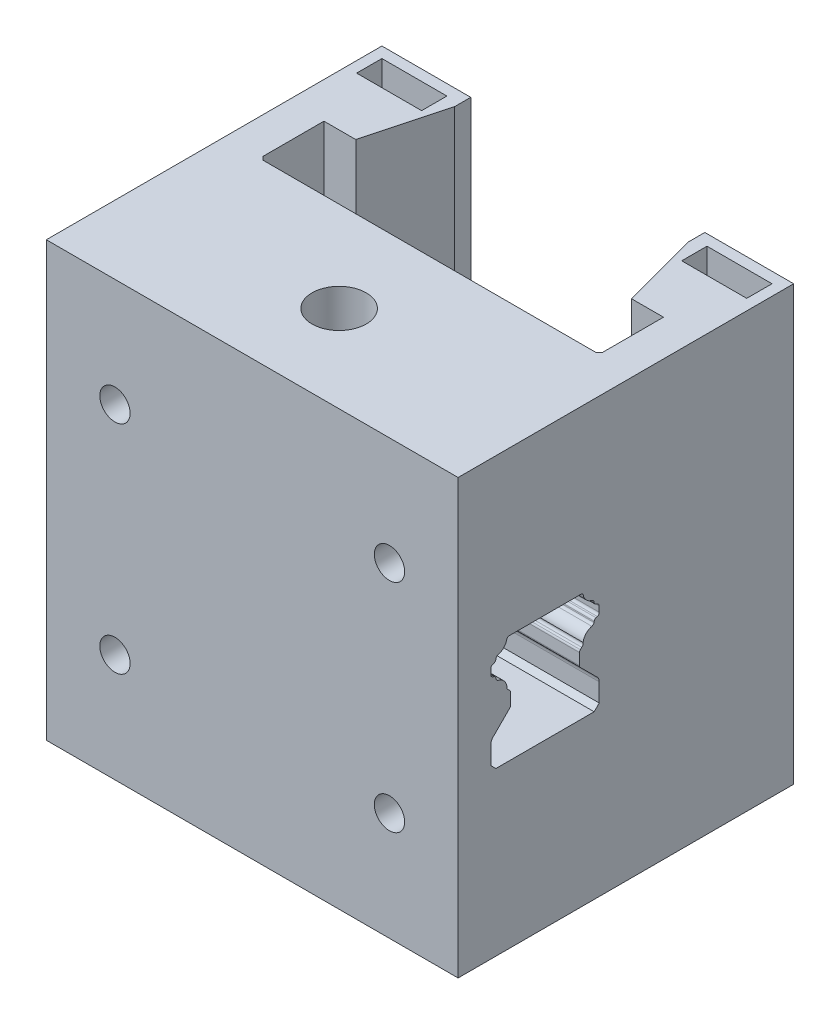
SolidWorks part; units mm, degrees
ref_plane "Front Plane" through (0, 0, 0) normal (0, 0, 1) x (1, 0, 0)
ref_plane "Top Plane" through (0, 0, 0) normal (0, 1, 0) x (1, 0, 0)
ref_plane "Right Plane" through (0, 0, 0) normal (1, 0, 0) x (0, 0, -1)
sketch "Sketch1" plane through (0, 0, 0) normal (0, 1, 0) x (1, 0, 0)
  line L0 (23.07, -9.85) -> (-23.07, -9.85)
  line L1 (-23.5, -9.42) -> (-23.07, -9.85)
  line L2 (-23.5, -9.42) -> (-23.5, -0.95)
  line L7 (-19.0939, -0.95) -> (-23.5, -0.95)
  line L8 (-19.0939, -0.95) -> (-19, -0.5997)
  line L9 (-16.2, 9.85) -> (-19, -0.5997)
  line L10 (16.2, 9.85) -> (-16.2, 9.85)
  line L11 (23.07, -9.85) -> (23.5, -9.42)
  line L12 (23.5, -2.9) -> (23.5, -9.42)
  line L13 (23.5, -2.9) -> (23.5, -0.95)
  line L15 (19.0939, -0.95) -> (23.5, -0.95)
  line L16 (19.0939, -0.95) -> (19, -0.5997)
  line L17 (16.2, 9.85) -> (19, -0.5997)
  line L18 (-28.5, -14.85) -> (28.5, -14.85)
  line L19 (-28.5, -14.85) -> (-28.5, 13.85)
  line L20 (-28.5, 13.85) -> (28.5, 13.85)
  line L21 (28.5, -14.85) -> (28.5, 13.85)
  dimension "D1" = 5
  dimension "D2" = 5
  dimension "D3" = 5
  dimension "D4" = 4
extrude "Boss-Extrude1" add sketch "Sketch1" along normal blind 60
sketch "Sketch2" plane through (0, 0, 0) normal (0, -1, 0) x (1, 0, 0)
  line L0 (0, -25.3794) -> (0, 27.4746) construction
  line L1 (28.5, -8.0706) -> (19.5, -8.0706)
  line L2 (28.5, -8.0706) -> (28.5, -12.0706)
  line L3 (28.5, -12.0706) -> (19.5, -12.0706)
  line L4 (19.5, -8.0706) -> (19.5, -12.0706)
  line L5 (-19.5, -8.0706) -> (-19.5, -12.0706)
  line L6 (-28.5, -12.0706) -> (-19.5, -12.0706)
  line L7 (-28.5, -8.0706) -> (-28.5, -12.0706)
  line L8 (-28.5, -8.0706) -> (-19.5, -8.0706)
  dimension "D1" = 9
  dimension "D2" = 4
extrude "Cut-Extrude1" cut sketch "Sketch2" against normal through all
sketch "Sketch5" plane through (0, 0, 0) normal (1, 0, 0) x (0, 0, -1)
  line L0 (-14.85, 23.2) -> (-14.85, 34.0815)
  line L1 (-15.55, 22.5) -> (-14.85, 23.2)
  line L2 (-29.15, 22.5) -> (-15.55, 22.5)
  line L3 (-29.85, 23.2) -> (-29.15, 22.5)
  line L4 (-29.85, 25.7434) -> (-29.85, 23.2)
  line L5 (-27.2372, 28.7704) -> (-29.5571, 26.4505)
  line L6 (-27.12, 30.6153) -> (-27.12, 29.0533)
  line L7 (-27.4316, 31.0926) -> (-27.2372, 30.8982)
  line L8 (-29.1562, 33.3541) -> (-29.1243, 33.2128)
  line L9 (-29.5857, 33.7052) -> (-29.4106, 33.6421)
  line L10 (-29.85, 34.8375) -> (-29.85, 34.0815)
  line L11 (-29.4277, 35.2633) -> (-29.5687, 35.2195)
  line L12 (-29.125, 35.7021) -> (-29.1553, 35.5612)
  line L13 (-27.399, 37.5) -> (-27.4361, 37.4629)
  line L14 (-17.301, 37.5) -> (-27.399, 37.5)
  line L15 (-17.2639, 37.4629) -> (-17.301, 37.5)
  line L16 (-15.5447, 35.5612) -> (-15.575, 35.7021)
  line L17 (-15.1313, 35.2195) -> (-15.2723, 35.2633)
  line L18 (-14.85, 34.0815) -> (-14.85, 60)
  line L19 (-15.2894, 33.6421) -> (-15.1143, 33.7052)
  line L20 (-15.5757, 33.2128) -> (-15.5438, 33.3541)
  line L21 (-17.4628, 30.8982) -> (-17.2684, 31.0926)
  line L22 (-17.58, 29.0533) -> (-17.58, 30.6153)
  line L23 (-15.1429, 26.4505) -> (-17.4628, 28.7704)
  line L24 (-14.85, 60) -> (-34.3805, 60)
  line L25 (-14.85, 30) -> (-29.85, 30) construction
  line L26 (-34.3805, 60) -> (-34.3805, 0)
  line L27 (-14.85, 34.0815) -> (-14.85, 30) construction
  line L28 (-34.3805, 0) -> (-14.85, 0)
  line L29 (-14.85, 0) -> (-14.85, 23.2)
  arc A0 (-14.85, 25.7434) -> (-15.1429, 26.4505) centre (-15.85, 25.7434) ccw
  arc A1 (-29.5571, 26.4505) -> (-29.85, 25.7434) centre (-28.85, 25.7434) ccw
  arc A2 (-27.2372, 28.7704) -> (-27.12, 29.0533) centre (-27.52, 29.0533) ccw
  arc A3 (-27.12, 30.6153) -> (-27.2372, 30.8982) centre (-27.52, 30.6153) ccw
  arc A4 (-27.6206, 31.5718) -> (-27.4316, 31.0926) centre (-27.2414, 31.4445) ccw
  arc A5 (-27.6206, 31.5718) -> (-28.8285, 32.9123) centre (-29.2062, 31.3576) ccw
  arc A6 (-29.1243, 33.2128) -> (-28.8285, 32.9123) centre (-28.7341, 33.301) ccw
  arc A7 (-29.1562, 33.3541) -> (-29.4106, 33.6421) centre (-29.5464, 33.2658) ccw
  arc A8 (-29.85, 34.0815) -> (-29.5857, 33.7052) centre (-29.45, 34.0815) ccw
  arc A9 (-29.5687, 35.2195) -> (-29.85, 34.8375) centre (-29.45, 34.8375) ccw
  arc A10 (-29.4277, 35.2633) -> (-29.1553, 35.5612) centre (-29.5464, 35.6453) ccw
  arc A11 (-28.8284, 36.0067) -> (-29.125, 35.7021) centre (-28.734, 35.618) ccw
  arc A12 (-28.8284, 36.0067) -> (-27.624, 37.3234) centre (-29.2062, 37.5614) ccw
  arc A13 (-27.4361, 37.4629) -> (-27.624, 37.3234) centre (-27.3021, 37.086) ccw
  arc A14 (-17.076, 37.3234) -> (-17.2639, 37.4629) centre (-17.3979, 37.086) ccw
  arc A15 (-17.076, 37.3234) -> (-15.8716, 36.0067) centre (-15.4938, 37.5614) ccw
  arc A16 (-15.575, 35.7021) -> (-15.8716, 36.0067) centre (-15.966, 35.618) ccw
  arc A17 (-15.5447, 35.5612) -> (-15.2723, 35.2633) centre (-15.1536, 35.6453) ccw
  arc A18 (-14.85, 34.8375) -> (-15.1313, 35.2195) centre (-15.25, 34.8375) ccw
  arc A19 (-15.1143, 33.7052) -> (-14.85, 34.0815) centre (-15.25, 34.0815) ccw
  arc A20 (-15.2894, 33.6421) -> (-15.5438, 33.3541) centre (-15.1536, 33.2658) ccw
  arc A21 (-15.8715, 32.9123) -> (-15.5757, 33.2128) centre (-15.9659, 33.301) ccw
  arc A22 (-15.8715, 32.9123) -> (-17.0794, 31.5718) centre (-15.4938, 31.3576) ccw
  arc A23 (-17.2684, 31.0926) -> (-17.0794, 31.5718) centre (-17.4586, 31.4445) ccw
  arc A24 (-17.4628, 30.8982) -> (-17.58, 30.6153) centre (-17.18, 30.6153) ccw
  arc A25 (-17.58, 29.0533) -> (-17.4628, 28.7704) centre (-17.18, 29.0533) ccw
  dimension "D1" = 15
  dimension "D2" = 7.5
extrude "Boss-Extrude2" add sketch "Sketch5" along normal mid plane 57 contours A18 L18 L24 L26 L28 L29 L1 L2 L3 L4 A1 L5 A2 L6 A3 L7 A4 A5 A6 L8 A7 L9 A8 L10 A9 L11 A10 L12 A11 A12 A13 L13 L14 L15 A14 A15 A16 L16 A17 L17 | L22 A25 L23 A0 L0 A19 L19 A20 L20 A21 A22 A23 L21 A24
sketch "Sketch6" plane through (0, 60, 0) normal (0, 1, 0) x (1, 0, 0)
  line L0 (0, 26.3935) -> (0, -49.3571) construction
  line L1 (28.5, 13.85) -> (-28.5, 13.85) construction
  line L2 (-7.75, 19.7454) -> (7.75, 19.7454)
  line L3 (-7.75, 19.7454) -> (-7.75, 4.3549)
  line L4 (-7.75, 4.3549) -> (7.75, 4.3549)
  line L5 (7.75, 19.7454) -> (7.75, 4.3549)
  dimension "D1" = 5.8954
  dimension "D2" = 15.5
extrude "Cut-Extrude2" cut sketch "Sketch6" against normal blind 80
sketch "Sketch9" plane through (0, 60, 0) normal (0, 1, 0) x (1, 0, 0)
  line L0 (-19.5, 13.85) -> (-19.5, 29.1706)
  line L1 (-19.5, 29.1706) -> (-28.5, 29.1706)
  line L2 (30.2, 1.2503) -> (30.2, 34.991) construction
  line L3 (-28.5, 23.1706) -> (-28.5, 8.0706) construction
  line L4 (-19.5, 12.0706) -> (-19.5, 8.0706) construction
  line L5 (-7.75, 13.85) -> (-28.5, 13.85) construction
  line L6 (-14.5, 13.85) -> (-14.5, 32.1706)
  line L7 (10, 28.7358) -> (570, 28.7358) construction
  line L10 (-14.5, 13.85) -> (-19.5, 13.85)
  line L11 (-19.25, 24.1706) -> (-28.75, 24.1706) construction
  line L12 (0, -34.3805) -> (0, 38.6423) construction
  line L13 (28.5, -34.3805) -> (-28.5, -34.3805) construction
  line L14 (-33.5, 26.1706) -> (-28.5, 26.1706)
  line L16 (-33.5, 32.1706) -> (-14.5, 32.1706)
  line L17 (-33.5, 26.1706) -> (-33.5, 32.1706)
  line L18 (-28.5, 26.1706) -> (-28.5, 29.1706)
  line L19 (28.5, 23.1706) -> (28.5, 8.0706) construction
  line L20 (30.2, 12.85) -> (30.2, 28.7358)
  line L21 (33.5, 12.85) -> (33.5, 32.1706)
  line L24 (33.5, 12.85) -> (30.2, 12.85)
  line L25 (14.5, 13.85) -> (19.5, 13.85)
  line L28 (14.5, 32.1706) -> (33.5, 32.1706)
  line L29 (14.5, 13.85) -> (14.5, 32.1706)
  line L31 (19.5, 28.7358) -> (30.2, 28.7358)
  line L32 (19.5, 13.85) -> (19.5, 28.7358)
  dimension "D1" = 5
  dimension "D2" = 3
  dimension "D3" = 3
  dimension "D4" = 5
  dimension "D5" = 5
extrude "Boss-Extrude5" add sketch "Sketch9" against normal up to surface (60 mm away) up to face at (0, 0, -2.4717)
sketch "Sketch10" plane through (0, 0, 34.3805) normal (0, 0, 1) x (1, 0, 0)
  line L0 (0, 60) -> (0, 0) construction
  line L1 (28.5, 60) -> (-28.5, 60) construction
  line L3 (-19, 45) -> (19, 45) construction
  line L4 (-19, 45) -> (-19, 15) construction
  line L5 (-19, 15) -> (19, 15) construction
  line L6 (19, 45) -> (19, 15) construction
  line L7 (-19, 45) -> (19, 15) construction
  line L8 (-19, 15) -> (19, 45) construction
  circle A0 centre (19, 45) radius 2.1
  circle A1 centre (19, 15) radius 2.1
  circle A2 centre (-19, 15) radius 2.1
  circle A3 centre (-19, 45) radius 2.1
  point P5 (0, 30)
  dimension "D3" = 4.2
  dimension "D1" = 30
  dimension "D2" = 38
extrude "Cut-Extrude3" cut sketch "Sketch10" against normal up to surface (24.5305 mm away) up to face at (0, 30, 9.85)
sketch "Sketch11" plane through (0, 0, 0) normal (0, -1, 0) x (1, 0, 0)
  line L0 (28.5, -13.85) -> (19.5, -13.85) construction
  line L1 (75.7263, -13.85) -> (13.7422, -13.85)
  line L2 (75.7263, -13.85) -> (75.7263, -57.0774)
  line L3 (75.7263, -57.0774) -> (13.7422, -57.0774)
  line L4 (13.7422, -13.85) -> (13.7422, -57.0774)
  line L6 (35.2, -11.2951) -> (29.2, -11.2951)
  line L7 (35.2, -11.2951) -> (35.2, -13.8378)
  line L8 (35.2, -13.8378) -> (29.2, -13.8378)
  line L9 (29.2, -11.2951) -> (29.2, -13.8378)
  line L12 (29.2, -1.2503) -> (29.2, -34.991) construction
extrude "Cut-Extrude4" cut sketch "Sketch11" against normal through all
sketch "Sketch12" plane through (0, 0, 0) normal (0, -1, 0) x (1, 0, 0)
  line L1 (18.2699, -7.1631) -> (28.5, -7.1631)
  line L2 (18.2699, -7.1631) -> (18.2699, -13.85)
  line L3 (18.2699, -13.85) -> (28.5, -13.85)
  line L4 (28.5, -7.1631) -> (28.5, -13.85)
sketch "Sketch13" plane through (0, 0, 0) normal (0, -1, 0) x (1, 0, 0)
  line L1 (35.6591, -15.3652) -> (29.6481, -15.3652)
  line L2 (35.6591, -15.3652) -> (35.6591, -12.7446)
  line L3 (35.6591, -12.7446) -> (29.6481, -12.7446)
  line L4 (29.6481, -15.3652) -> (29.6481, -12.7446)
extrude "Cut-Extrude5" cut sketch "Sketch13" against normal through all
sketch "Sketch14" plane through (0, 0, 0) normal (0, -1, 0) x (-1, 0, 0)
  line L1 (-28.5, 12.0706) -> (-19.5, 12.0706)
  line L2 (-28.5, 12.0706) -> (-28.5, 8.0706)
  line L3 (-28.5, 8.0706) -> (-19.5, 8.0706)
  line L4 (-19.5, 12.0706) -> (-19.5, 8.0706)
extrude "Boss-Extrude7" add sketch "Sketch14" against normal through all
extrude "Boss-Extrude6" add sketch "Sketch12" against normal through all
sketch "Sketch15" plane through (0, 60, 0) normal (0, 1, 0) x (1, 0, 0)
  line L1 (-28.5, 8.0706) -> (-19.5, 8.0706)
  line L2 (-28.5, 8.0706) -> (-28.5, 12.0706)
  line L3 (-28.5, 12.0706) -> (-19.5, 12.0706)
  line L4 (-19.5, 8.0706) -> (-19.5, 12.0706)
extrude "Boss-Extrude8" add sketch "Sketch15" against normal through all
sketch "Sketch16" plane through (0, 60, 0) normal (0, 1, 0) x (1, 0, 0)
  line L0 (-28.5, 13.85) -> (-28.5, -34.3805) construction
  line L1 (-19.5, 13.85) -> (-28.5, 13.85)
  line L2 (-19.5, 13.85) -> (-19.5, 12.07)
  line L3 (-19.5, 12.07) -> (-28.5, 12.07)
  line L4 (-28.5, 13.85) -> (-28.5, 12.07)
  dimension "D1" = 1.78
extrude "Cut-Extrude6" cut sketch "Sketch16" against normal through all
sketch "Sketch17" plane through (0, 60, 0) normal (0, 1, 0) x (1, 0, 0)
  line L0 (-28.5, 12.07) -> (-19.5, 12.07) construction
  line L1 (-33.5, 12.07) -> (-7.75, 12.07)
  line L2 (-33.5, 12.07) -> (-33.5, 32.1706)
  line L3 (-33.5, 32.1706) -> (-7.75, 32.1706)
  line L4 (-7.75, 12.07) -> (-7.75, 32.1706)
  line L5 (-7.75, 13.85) -> (-7.75, 9.85) construction
extrude "Cut-Extrude7" cut sketch "Sketch17" against normal through all
sketch "Sketch18" plane through (0, 60, 0) normal (0, 1, 0) x (1, 0, 0)
  line L1 (-16.2, 9.85) -> (16.2, 9.85)
  line L2 (-16.2, 9.85) -> (-16.2, 22.4633)
  line L3 (-16.2, 22.4633) -> (16.2, 22.4633)
  line L4 (16.2, 9.85) -> (16.2, 22.4633)
extrude "Cut-Extrude8" cut sketch "Sketch18" against normal through all
sketch "Sketch19" plane through (0, 60, 0) normal (0, 1, 0) x (1, 0, 0)
  line L0 (28.5, -34.3805) -> (28.5, 13.85) construction
  line L1 (-28.5, 12.07) -> (28.5, 12.07)
  line L2 (-28.5, 12.07) -> (-28.5, 16.0198)
  line L3 (-28.5, 16.0198) -> (28.5, 16.0198)
  line L4 (28.5, 12.07) -> (28.5, 16.0198)
extrude "Cut-Extrude9" cut sketch "Sketch19" against normal through all
sketch "Sketch20" plane through (0, 60, 0) normal (0, 1, 0) x (1, 0, 0)
  line L0 (-28.5, 12.07) -> (-16.2, 12.07) construction
  line L1 (-27, 10.57) -> (-18, 10.57)
  line L2 (-27, 10.57) -> (-27, 7.07)
  line L3 (-27, 7.07) -> (-18, 7.07)
  line L4 (-18, 10.57) -> (-18, 7.07)
  line L5 (-28.5, 12.07) -> (-28.5, -34.3805) construction
  line L6 (0, -1009.85) -> (0, 48990.15) construction
  line L7 (-23.07, -9.85) -> (23.07, -9.85) construction
  line L8 (18, 10.57) -> (18, 7.07)
  line L9 (27, 7.07) -> (18, 7.07)
  line L10 (27, 10.57) -> (27, 7.07)
  line L11 (27, 10.57) -> (18, 10.57)
  point P13 (0, -9.85)
  dimension "D1" = 9
  dimension "D2" = 1.5
  dimension "D3" = 3.5
  dimension "D4" = 1.5
extrude "Cut-Extrude10" cut sketch "Sketch20" against normal through all
sketch "Sketch21" plane through (0, 0, -12.07) normal (0, 0, -1) x (-1, 0, 0)
  line L0 (28.5, 0) -> (16.2, 0) construction
  line L1 (18, 50) -> (27, 50)
  line L2 (18, 50) -> (18, 46.5)
  line L3 (18, 46.5) -> (27, 46.5)
  line L4 (27, 50) -> (27, 46.5)
  line L5 (18, 13.5) -> (27, 13.5)
  line L6 (18, 13.5) -> (18, 10)
  line L7 (18, 10) -> (27, 10)
  line L8 (27, 13.5) -> (27, 10)
  line L9 (28.5, 60) -> (16.2, 60) construction
  line L10 (28.5, 0) -> (28.5, 60) construction
  line L11 (0, 60) -> (0, 0) construction
  line L12 (23.07, 60) -> (-23.07, 60) construction
  line L13 (-27, 13.5) -> (-27, 10)
  line L14 (-18, 10) -> (-27, 10)
  line L15 (-18, 13.5) -> (-18, 10)
  line L16 (-18, 13.5) -> (-27, 13.5)
  line L17 (-27, 50) -> (-27, 46.5)
  line L18 (-18, 46.5) -> (-27, 46.5)
  line L19 (-18, 50) -> (-18, 46.5)
  line L20 (-18, 50) -> (-27, 50)
  line L21 (27, 13.5) -> (27, 10)
  dimension "D1" = 3.5
  dimension "D2" = 3.5
  dimension "D3" = 10
  dimension "D4" = 10
  dimension "D5" = 1.5
  dimension "D6" = 9
extrude "Cut-Extrude11" cut sketch "Sketch21" against normal up to surface (1.5 mm away) contours L19 L20 L17 L18 | L4 L1 L2 L3 | L8 L5 L6 L7 | L15 L16 L13 L14 up to face at (22.5, 30, -10.57)
sketch "Sketch23" plane through (0, 22.5, 0) normal (0, 1, 0) x (1, 0, 0)
  line L0 (-28.5, -22.35) -> (28.5, -22.35) construction
  line L1 (-28.5, 12.07) -> (-28.5, -34.3805) construction
  line L2 (28.5, -34.3805) -> (28.5, 12.07) construction
  line L4 (-28.5, -15.55) -> (-28.5, -29.15) construction
  line L5 (-28.5, -29.15) -> (-28.5, -15.55) construction
  circle A0 centre (0, -22.35) radius 3.75
  dimension "D1" = 7.5
extrude "Cut-Extrude12" cut sketch "Sketch23" along normal through all
sketch "Sketch24" plane through (0, 22.5, 0) normal (0, 1, 0) x (1, 0, 0)
  circle A0 centre (0, -22.35) radius 2
  dimension "D1" = 4
extrude "Cut-Extrude13" cut sketch "Sketch24" against normal through all
